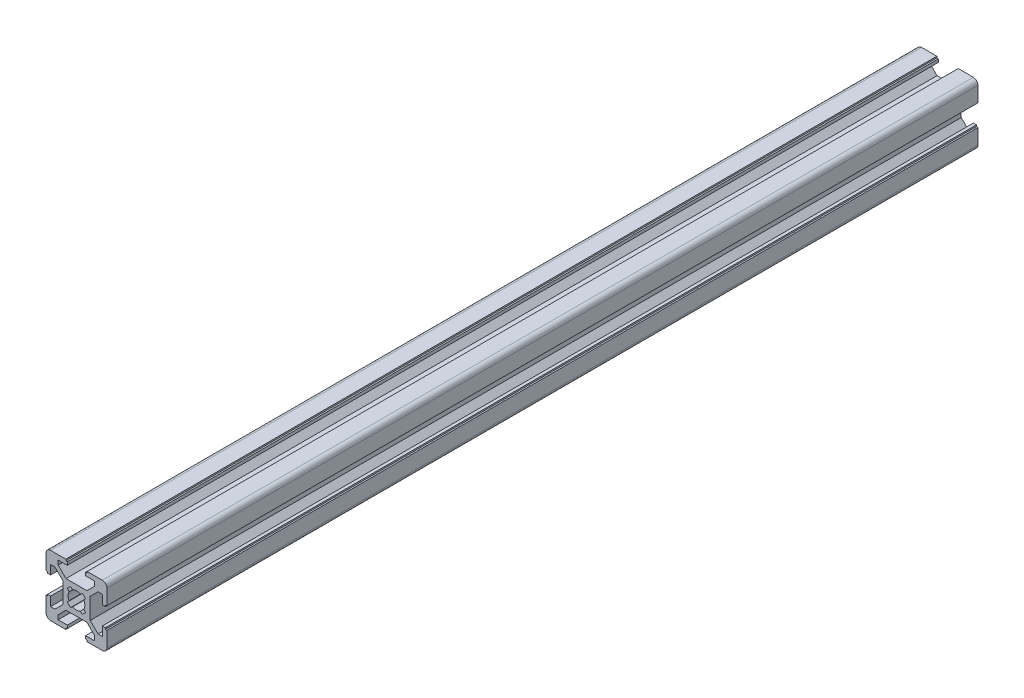
SolidWorks part; units mm, degrees
ref_plane "Ebene vorne" through (0, 0, 0) normal (0, 0, 1) x (1, 0, 0)
ref_plane "Ebene oben" through (0, 0, 0) normal (0, 1, 0) x (1, 0, 0)
ref_plane "Ebene rechts" through (0, 0, 0) normal (1, 0, 0) x (0, 0, -1)
sketch "Skizze1" plane through (0, 0, 0) normal (0, 0, 1) x (1, 0, 0)
  line L0 (-2.539, 1.0906) -> (-3.1036, 1.7634)
  line L1 (-3.1036, -2.1357) -> (-2.539, -1.4629)
  line L2 (-2.053, -3.1863) -> (-3.1036, -2.1357)
  line L3 (-1.3802, -2.6218) -> (-2.053, -3.1863)
  line L4 (1.8462, -3.1863) -> (1.1734, -2.6218)
  line L5 (2.8968, -2.1357) -> (1.8462, -3.1863)
  line L6 (2.3323, -1.4629) -> (2.8968, -2.1357)
  line L7 (2.8968, 1.7634) -> (2.3323, 1.0906)
  line L8 (1.8462, 2.814) -> (2.8968, 1.7634)
  line L9 (1.1734, 2.2495) -> (1.8462, 2.814)
  line L10 (-2.053, 2.814) -> (-1.3802, 2.2495)
  line L11 (-3.1036, 1.7634) -> (-2.053, 2.814)
  line L12 (9.8966, -8.6862) -> (9.8966, -3.6862)
  line L13 (9.8966, -3.6862) -> (9.3966, -3.6862)
  line L14 (9.3966, -3.6862) -> (9.3966, -3.1862)
  line L15 (9.3966, -3.1862) -> (8.3966, -3.1862)
  line L16 (8.3966, -3.1862) -> (8.3966, -6.1862)
  line L17 (8.3966, -6.1862) -> (6.9573, -6.1862)
  line L18 (6.9573, -6.1862) -> (4.3966, -3.6255)
  line L19 (4.3966, -3.6255) -> (4.3966, 3.2532)
  line L20 (4.3966, 3.2532) -> (6.9573, 5.8138)
  line L21 (6.9573, 5.8138) -> (8.3966, 5.8138)
  line L22 (8.3966, 5.8138) -> (8.3966, 2.8138)
  line L23 (8.3966, 2.8138) -> (9.3966, 2.8138)
  line L24 (9.3966, 2.8138) -> (9.3966, 3.3138)
  line L25 (9.3966, 3.3138) -> (9.8966, 3.3138)
  line L26 (9.8966, 3.3138) -> (9.8966, 8.3138)
  line L27 (8.3966, 9.8138) -> (3.3966, 9.8138)
  line L28 (3.3966, 9.8138) -> (3.3966, 9.3138)
  line L29 (3.3966, 9.3138) -> (2.8966, 9.3138)
  line L30 (2.8966, 9.3138) -> (2.8966, 8.3138)
  line L31 (2.8966, 8.3138) -> (5.8966, 8.3138)
  line L32 (5.8966, 8.3138) -> (5.8966, 6.8745)
  line L33 (5.8966, 6.8745) -> (3.336, 4.3138)
  line L34 (3.336, 4.3138) -> (-3.5427, 4.3138)
  line L35 (-3.5427, 4.3138) -> (-6.1034, 6.8745)
  line L36 (-6.1034, 6.8745) -> (-6.1034, 8.3138)
  line L37 (-6.1034, 8.3138) -> (-3.1034, 8.3138)
  line L38 (-3.1034, 8.3138) -> (-3.1034, 9.3138)
  line L39 (-3.1034, 9.3138) -> (-3.6034, 9.3138)
  line L40 (-3.6034, 9.3138) -> (-3.6034, 9.8138)
  line L41 (-3.6034, 9.8138) -> (-8.6034, 9.8138)
  line L42 (-10.1034, 8.3138) -> (-10.1034, 3.3138)
  line L43 (-10.1034, 3.3138) -> (-9.6034, 3.3138)
  line L44 (-9.6034, 3.3138) -> (-9.6034, 2.8138)
  line L45 (-9.6034, 2.8138) -> (-8.6034, 2.8138)
  line L46 (-8.6034, 2.8138) -> (-8.6034, 5.8138)
  line L47 (-8.6034, 5.8138) -> (-7.164, 5.8138)
  line L48 (-7.164, 5.8138) -> (-4.6034, 3.2532)
  line L49 (-4.6034, 3.2532) -> (-4.6034, -3.6255)
  line L50 (-4.6034, -3.6255) -> (-7.164, -6.1862)
  line L51 (-7.164, -6.1862) -> (-8.6034, -6.1862)
  line L52 (-8.6034, -6.1862) -> (-8.6034, -3.1862)
  line L53 (-8.6034, -3.1862) -> (-9.6034, -3.1862)
  line L54 (-9.6034, -3.1862) -> (-9.6034, -3.6862)
  line L55 (-9.6034, -3.6862) -> (-10.1034, -3.6862)
  line L56 (-10.1034, -3.6862) -> (-10.1034, -8.6862)
  line L57 (-8.6034, -10.1862) -> (-3.6034, -10.1862)
  line L58 (-3.6034, -10.1862) -> (-3.6034, -9.6862)
  line L59 (-3.6034, -9.6862) -> (-3.1034, -9.6862)
  line L60 (-3.1034, -9.6862) -> (-3.1034, -8.6862)
  line L61 (-3.1034, -8.6862) -> (-6.1034, -8.6862)
  line L62 (-6.1034, -8.6862) -> (-6.1034, -7.2468)
  line L63 (-6.1034, -7.2468) -> (-3.5427, -4.6862)
  line L64 (-3.5427, -4.6862) -> (3.336, -4.6862)
  line L65 (3.336, -4.6862) -> (5.8966, -7.2468)
  line L66 (5.8966, -7.2468) -> (5.8966, -8.6862)
  line L67 (5.8966, -8.6862) -> (2.8966, -8.6862)
  line L68 (2.8966, -8.6862) -> (2.8966, -9.6862)
  line L69 (2.8966, -9.6862) -> (3.3966, -9.6862)
  line L70 (3.3966, -9.6862) -> (3.3966, -10.1862)
  line L71 (3.3966, -10.1862) -> (8.3966, -10.1862)
  arc A0 (8.3966, -10.1862) -> (9.8966, -8.6862) centre (8.3966, -8.6862) ccw
  arc A1 (9.8966, 8.3138) -> (8.3966, 9.8138) centre (8.3966, 8.3138) ccw
  arc A2 (-8.6034, 9.8138) -> (-10.1034, 8.3138) centre (-8.6034, 8.3138) ccw
  arc A3 (-10.1034, -8.6862) -> (-8.6034, -10.1862) centre (-8.6034, -8.6862) ccw
  arc A4 (-2.539, 1.0906) -> (-2.539, -1.4629) centre (-0.1034, -0.1862) ccw
  arc A5 (-1.3802, -2.6218) -> (1.1734, -2.6218) centre (-0.1034, -0.1862) ccw
  arc A6 (2.3323, -1.4629) -> (2.3323, 1.0906) centre (-0.1034, -0.1862) ccw
  arc A7 (1.1734, 2.2495) -> (-1.3802, 2.2495) centre (-0.1034, -0.1862) ccw
extrude "Aufsatz-Linear austragen1" add sketch "Skizze1" along normal blind 286
